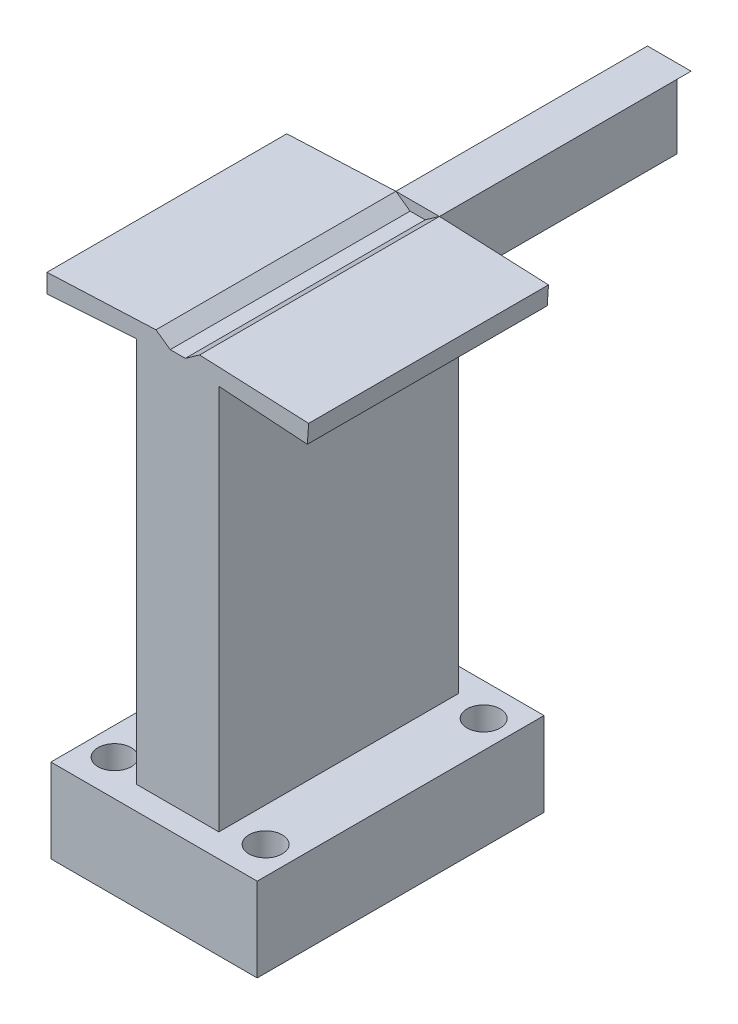
SolidWorks part; units mm, degrees
ref_plane "Alzado" through (0, 0, 0) normal (0, 0, 1) x (1, 0, 0)
ref_plane "Planta" through (0, 0, 0) normal (0, 1, 0) x (1, 0, 0)
ref_plane "Vista lateral" through (0, 0, 0) normal (1, 0, 0) x (0, 0, -1)
sketch "Croquis2" plane through (0, 0, 0) normal (0, 0, 1) x (1, 0, 0)
  line L0 (0, 0) -> (0, 10.414)
  line L1 (0, 10.414) -> (2.159, 11.938)
  line L2 (2.159, 11.938) -> (-4.445, 11.938)
  line L3 (-4.445, 11.938) -> (-2.286, 10.414)
  line L4 (-2.286, 10.414) -> (-2.286, 0)
  line L5 (-2.286, 0) -> (0, 0)
  dimension "D1" = 2.286
  dimension "D2" = 10.414
  dimension "D3" = 10.414
  dimension "D4" = 6.604
  dimension "D5" = 1.524
  dimension "D6" = 2.159
extrude "Saliente-Extruir1" add sketch "Croquis2" along normal blind 38.1
sketch "Croquis3" plane through (0, 0, 38.1) normal (0, 0, 1) x (1, 0, 0)
  line L6 (-7.366, -49.1429) -> (-7.366, 9.189)
  line L7 (5.08, 9.2771) -> (5.08, -49.1429)
  line L10 (-2.286, 10.414) -> (0, 10.414)
  line L12 (-7.366, -49.1429) -> (5.08, -49.1429)
  line L17 (-2.286, 10.414) -> (-4.445, 11.938)
  line L18 (0, 10.414) -> (2.159, 11.938)
  line L22 (-2.286, 10.414) -> (-2.286, 0) construction
  line L23 (-4.445, 11.938) -> (-20.955, 11.2229)
  line L25 (-4.445, 11.938) -> (-38.4024, 10.4673) construction
  line L26 (2.159, 11.938) -> (18.669, 11.2229)
  line L27 (2.159, 11.938) -> (36.1164, 10.4673) construction
  line L31 (-20.955, 11.2229) -> (-20.955, 8.3694)
  line L32 (-7.4562, 9.2771) -> (-46.4201, 6.6569) construction
  line L33 (-20.955, 8.3694) -> (-7.4562, 9.2771)
  line L34 (-7.4562, 9.2771) -> (-7.366, 9.189)
  line L35 (18.669, 11.2229) -> (18.478, 8.3822)
  line L36 (5.1702, 9.2771) -> (44.1341, 6.6569) construction
  line L37 (18.478, 8.3822) -> (5.1702, 9.2771)
  line L38 (5.1702, 9.2771) -> (5.08, 9.2771)
  point P5 (0, 0)
  point P28 (-7.366, -59.3029)
  point P29 (5.08, -59.3029)
  dimension "D1" = 5.08
  dimension "D2" = 12.446
  dimension "D3" = 58.42
  dimension "D4" = 58.42
  dimension "D5" = 16.51
  dimension "D6" = 16.51
  dimension "D7" = 0.0902
extrude "Saliente-Extruir2" add sketch "Croquis3" along normal blind 36.322 separate body
sketch "Croquis5" plane through (0, -49.1429, 0) normal (0, -1, 0) x (1, 0, 0)
  line L8 (-16.8008, 77.978) -> (14.4412, 77.978)
  line L9 (14.4412, 77.978) -> (14.4412, 34.544)
  line L10 (14.4412, 34.544) -> (-16.8008, 34.544)
  line L11 (-16.8008, 34.544) -> (-16.8008, 77.978)
  line L13 (5.1702, 74.422) -> (5.1702, 38.1) construction
  line L16 (5.1702, 38.1) -> (18.478, 38.1) construction
  dimension "D1" = 31.242
  dimension "D2" = 43.434
  dimension "D3" = 9.271
  dimension "D4" = 3.556
extrude "Saliente-Extruir3" add sketch "Croquis5" along normal blind 12.7
sketch "Croquis6" plane through (0, -61.8429, 0) normal (0, -1, 0) x (1, 0, 0)
  line L0 (14.4412, 77.978) -> (-16.8008, 77.978) construction
  line L3 (14.4412, 34.544) -> (14.4412, 77.978) construction
  circle A0 centre (-12.6098, 72.517) radius 2.5146
  circle A1 centre (10.2502, 72.517) radius 2.5146
  circle A2 centre (10.2502, 39.5013) radius 2.5146
  circle A3 centre (-12.6098, 39.5013) radius 2.5146
  point P8 (0, 0)
  point P12 (0, 0)
  point P13 (0, 0)
  point P16 (0, 0)
  dimension "D1" = 5.0292
  dimension "D2" = 5.0292
  dimension "D3" = 5.0292
  dimension "D4" = 5.0292
  dimension "D5" = 22.86
  dimension "D6" = 33.0157
  dimension "D8" = 4.191
  dimension "D7" = 5.461
extrude "Cortar-Extruir6" cut sketch "Croquis6" against normal blind 13.97
